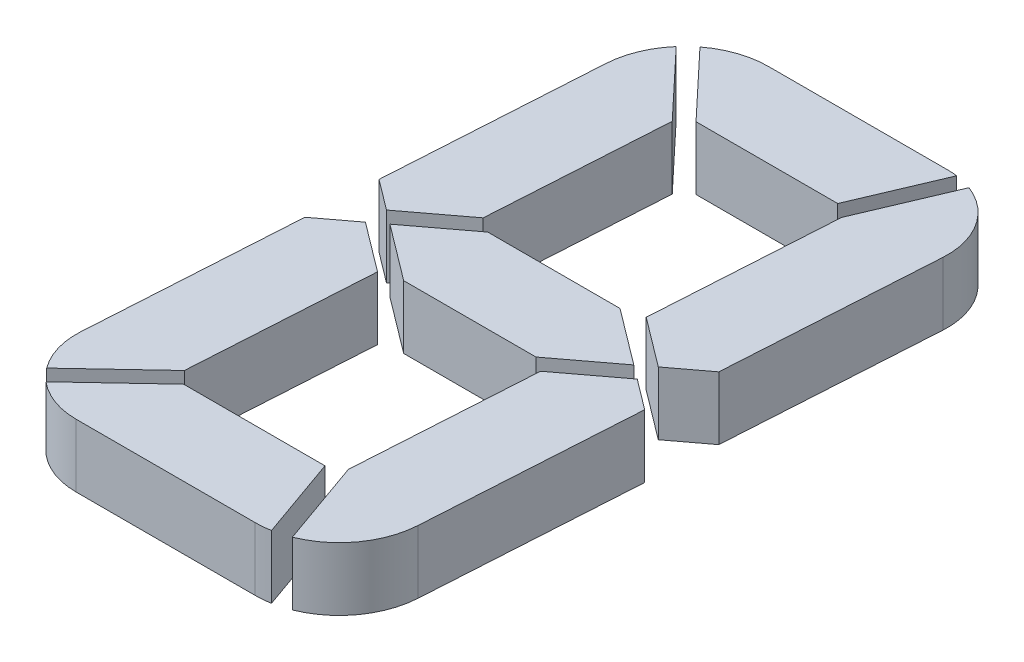
SolidWorks part; units mm, degrees
ref_plane "Front Plane" through (0, 0, 0) normal (0, 0, 1) x (1, 0, 0)
ref_plane "Top Plane" through (0, 0, 0) normal (0, 1, 0) x (1, 0, 0)
ref_plane "Right Plane" through (0, 0, 0) normal (1, 0, 0) x (0, 0, -1)
sketch "Sketch2" plane through (0, 0, 0) normal (0, 1, 0) x (1, 0, 0)
  line L0 (9.3918, 23) -> (12.6392, 30.6504) construction
  line L1 (8.0012, 23) -> (11.3715, 30.9397) construction
  line L2 (-17.4418, -23.5727) -> (-14.5634, 23.4884) construction
  line L3 (14.5634, -23.4884) -> (17.4418, 23.5727) construction
  line L4 (-6.5783, 31) -> (10.4548, 31) construction
  line L5 (-10.4548, -31) -> (6.5783, -31) construction
  line L6 (-6.5783, 23) -> (9.3918, 23) construction
  line L7 (-9.3918, -23) -> (6.5783, -23) construction
  line L8 (-9.3918, -23) -> (-8.2297, -4) construction
  line L9 (9.3333, 22.0431) -> (12.9414, 30.5435) construction
  line L10 (6.5783, -23) -> (9.2488, -30.5411) construction
  line L11 (6.5783, -23) -> (7.7404, -4) construction
  line L12 (-7.7404, 4) -> (8.2297, 4) construction
  line L13 (-8.2297, -4) -> (7.7404, -4) construction
  line L14 (-6.5783, 23) -> (-12.0598, 28.827) construction
  line L15 (8.2297, 4) -> (9.3918, 23) construction
  line L16 (5.2204, -23) -> (8.0078, -30.8713) construction
  line L17 (-7.7404, 4) -> (-6.5783, 23) construction
  line L18 (-9.3918, -23) -> (-18.0557, -31.1502) construction
  line L19 (-11.4496, 29.3459) -> (-5.48, 23) construction
  line L20 (-12.615, 28.2496) -> (-6.6454, 21.9037) construction
  line L21 (-14.9719, -29.3476) -> (-8.2242, -23) construction
  line L22 (-16.0682, -28.1822) -> (-9.3205, -21.8346) construction
  line L23 (6.6283, -22.1826) -> (9.5483, -30.4283) construction
  line L24 (-11.6, 0) -> (-6.2918, 4) construction
  line L25 (-11.6, 0) -> (-6.2918, -4) construction
  line L26 (11.6, 0) -> (6.2918, 4) construction
  line L27 (11.6, 0) -> (6.2918, -4) construction
  line L28 (-7.6819, 4.9559) -> (-12.9293, 1.0017) construction
  line L29 (-12.9293, 1.0017) -> (-15.8061, 3.1696) construction
  line L30 (-16.2126, -3.4758) -> (-12.9293, -1.0017) construction
  line L31 (-12.9293, -1.0017) -> (-8.2615, -4.5192) construction
  line L32 (7.6819, -4.9559) -> (12.9293, -1.0017) construction
  line L33 (12.9293, -1.0017) -> (15.8061, -3.1696) construction
  line L34 (8.2615, 4.5192) -> (12.9293, 1.0017) construction
  line L35 (12.9293, 1.0017) -> (16.2126, 3.4758) construction
  line L36 (-19, -32.5) -> (-19, 32.5) construction
  line L37 (19, -32.5) -> (19, 32.5) construction
  line L38 (-19, 32.5) -> (19, 32.5) construction
  line L39 (-19, -32.5) -> (19, -32.5) construction
  line L40 (-16.8257, -13.5) -> (15.1743, -13.5) construction
  line L41 (-15.1743, 13.5) -> (16.8257, 13.5) construction
  line L42 (16.7794, 27) -> (-13.5065, 27) construction
  line L43 (-10.4548, -31) -> (13.8794, -31) construction
  line L44 (13.5065, -27) -> (-16.7794, -27) construction
  line L45 (10.1479, -30.1595) -> (13.8353, 30.1296) construction
  line L46 (-10.1479, 30.1595) -> (-13.8353, -30.1296) construction
  line L47 (-1.896, -31) -> (1.896, 31) construction
  arc A0 (-6.5783, 31) -> (-14.5634, 23.4884) centre (-6.5783, 23) ccw construction
  arc A1 (14.5634, -23.4884) -> (6.5783, -31) centre (6.5783, -23) cw construction
  arc A2 (17.4418, 23.5727) -> (10.4548, 31) centre (10.4548, 24) ccw construction
  arc A3 (-10.4548, -31) -> (-17.4418, -23.5727) centre (-10.4548, -24) cw construction
  point P0 (-16, 0)
  point P3 (-16, 0)
  point P8 (16, 0)
  point P42 (-11.6, 0)
  point P43 (11.6, 0)
  point P67 (7.1594, -13.5)
  point P70 (-7.1594, 13.5)
  point P72 (1.9383, 31)
  point P85 (1.6364, 27)
  point P86 (-12.8182, -13.5)
  point P87 (-11.1668, 13.5)
  point P88 (-1.6364, -27)
  point P89 (12.8182, 13.5)
  point P90 (11.1668, -13.5)
  dimension "D6" = 8
  dimension "D8" = 7
  dimension "D3" = 86.5
  dimension "D5" = 16
  dimension "D4" = 16
  dimension "D7" = 8
  dimension "D11" = 0.8
  dimension "D12" = 0.8
  dimension "D13" = 0.8
  dimension "D14" = 0.8
  dimension "D9" = 4
  dimension "D10" = 4
  dimension "D2" = 31
  dimension "D15" = 31
  dimension "D16" = 113
  dimension "D17" = 1.6
  dimension "D18" = 0.32
  dimension "D19" = 109.5
  dimension "D20" = 1.6
  dimension "D21" = 0.32
  dimension "D22" = 4.4
  dimension "D23" = 143
  dimension "D24" = 4.4
  dimension "D25" = 143
  dimension "D26" = 1.6
  dimension "D27" = 1.6
  dimension "D28" = 1.6
  dimension "D29" = 1.6
  dimension "D32" = 1.5
  dimension "D33" = 1.5
  dimension "D34" = 4
  dimension "D35" = 4
  dimension "D36" = 4
  dimension "D37" = 4
  dimension "D30" = 19
  dimension "D31" = 19
sketch "Sketch3" plane through (0, 0, 0) normal (0, 1, 0) x (1, 0, 0)
  line L0 (-15.8061, 3.1696) -> (-14.5634, 23.4884)
  line L1 (-15.8061, 3.1696) -> (-12.9293, 1.0017)
  line L2 (-12.9293, 1.0017) -> (-7.6819, 4.9559)
  line L3 (-7.6819, 4.9559) -> (-6.6454, 21.9037)
  line L4 (-6.6454, 21.9037) -> (-12.615, 28.2496)
  line L5 (-11.4496, 29.3459) -> (-5.48, 23)
  line L6 (-5.48, 23) -> (8.0012, 23)
  line L7 (8.0012, 23) -> (11.3715, 30.9397)
  line L8 (-6.5783, 31) -> (10.4548, 31)
  line L9 (-11.6, 0) -> (-6.2918, 4)
  line L10 (-6.2918, 4) -> (6.2918, 4)
  line L11 (6.2918, 4) -> (11.6, 0)
  line L12 (11.6, 0) -> (6.2918, -4)
  line L13 (6.2918, -4) -> (-6.2918, -4)
  line L14 (-6.2918, -4) -> (-11.6, 0)
  line L15 (9.3333, 22.0431) -> (12.9414, 30.5435)
  line L16 (9.3333, 22.0431) -> (8.2615, 4.5192)
  line L17 (8.2615, 4.5192) -> (12.9293, 1.0017)
  line L18 (12.9293, 1.0017) -> (16.2126, 3.4758)
  line L19 (16.2126, 3.4758) -> (17.4418, 23.5727)
  line L20 (6.6283, -22.1826) -> (7.6819, -4.9559)
  line L21 (7.6819, -4.9559) -> (12.9293, -1.0017)
  line L22 (12.9293, -1.0017) -> (15.8061, -3.1696)
  line L23 (15.8061, -3.1696) -> (14.5634, -23.4884)
  line L24 (6.6283, -22.1826) -> (9.5483, -30.4283)
  line L25 (8.0078, -30.8713) -> (5.2204, -23)
  line L26 (5.2204, -23) -> (-8.2242, -23)
  line L27 (-8.2242, -23) -> (-14.9719, -29.3476)
  line L28 (-16.0682, -28.1822) -> (-9.3205, -21.8346)
  line L29 (-9.3205, -21.8346) -> (-8.2615, -4.5192)
  line L30 (-8.2615, -4.5192) -> (-12.9293, -1.0017)
  line L31 (-12.9293, -1.0017) -> (-16.2126, -3.4758)
  line L32 (-16.2126, -3.4758) -> (-17.4418, -23.5727)
  line L33 (-10.4548, -31) -> (6.5783, -31)
  line L34 (-19, 32.5) -> (19, 32.5)
  line L35 (19, 32.5) -> (19, -32.5)
  line L36 (19, -32.5) -> (-19, -32.5)
  line L37 (-19, -32.5) -> (-19, 32.5)
  arc A0 (-14.5634, 23.4884) -> (-12.615, 28.2496) centre (-6.5783, 23) cw
  arc A1 (-11.4496, 29.3459) -> (-6.5783, 31) centre (-6.5783, 23) cw
  arc A2 (10.4548, 31) -> (11.3715, 30.9397) centre (10.4548, 24) cw
  arc A3 (12.9414, 30.5435) -> (17.4418, 23.5727) centre (10.4548, 24) cw
  arc A5 (9.5483, -30.4283) -> (14.5634, -23.4884) centre (6.5783, -23) ccw
  arc A6 (8.0078, -30.8713) -> (6.5783, -31) centre (6.5783, -23) cw
  arc A7 (-10.4548, -31) -> (-14.9719, -29.3476) centre (-10.4548, -24) cw
  arc A8 (-16.0682, -28.1822) -> (-17.4418, -23.5727) centre (-10.4548, -24) cw
extrude "Boss-Extrude1" add sketch "Sketch3" against normal blind 6 contours A0 L0 L1 L2 L3 L4 | A2 L8 A1 L5 L6 L7 | A3 L15 L16 L17 L18 L19 | L14 L13 L12 L11 L10 L9 | A8 L28 L29 L30 L31 L32 | A7 L33 A6 L25 L26 L27 | L24 A5 L23 L22 L21 L20
equation "\"D4@Sketch2\"=\"D5@Sketch2\""
equation "\"D7@Sketch2\"=\"D6@Sketch2\""
equation "\"D11@Sketch2\"=\"D6@Sketch2\"/10"
equation "\"D12@Sketch2\"=\"D11@Sketch2\""
equation "\"D13@Sketch2\"=\"D11@Sketch2\""
equation "\"D14@Sketch2\"=\"D13@Sketch2\""
equation "\"D9@Sketch2\"=\"D6@Sketch2\"/2"
equation "\"D10@Sketch2\"=\"D9@Sketch2\""
equation "\"D15@Sketch2\"=\"D2@Sketch2\""
equation "\"D17@Sketch2\"=\"D12@Sketch2\"*2"
equation "\"D18@Sketch2\"=\"D17@Sketch2\"/5"
equation "\"D19@Sketch2\"=\"D16@Sketch2\"-(90-\"D3@Sketch2\")"
equation "\"D20@Sketch2\"=\"D17@Sketch2\""
equation "\"D21@Sketch2\"=\"D18@Sketch2\""
equation "\"D22@Sketch2\"=\"D6@Sketch2\"*0.55"
equation "\"D24@Sketch2\"=\"D22@Sketch2\""
equation "\"D25@Sketch2\"=\"D23@Sketch2\""
equation "\"D26@Sketch2\"=\"D17@Sketch2\""
equation "\"D27@Sketch2\"=\"D26@Sketch2\""
equation "\"D28@Sketch2\"=\"D27@Sketch2\""
equation "\"D29@Sketch2\"=\"D28@Sketch2\""
equation "\"D33@Sketch2\"=\"D32@Sketch2\""
equation "\"D34@Sketch2\"=\"D6@Sketch2\"/2"
equation "\"D35@Sketch2\"=\"D34@Sketch2\""
equation "\"D36@Sketch2\"=\"D34@Sketch2\""
equation "\"D37@Sketch2\"=\"D34@Sketch2\""
equation "\"D31@Sketch2\"=\"D30@Sketch2\""
equation "\"D3@Sketch5\"=\"D2@Sketch5\""
equation "\"D4@Sketch5\"=\"D2@Sketch5\""
equation "\"D5@Sketch5\"=\"D4@Sketch5\""
